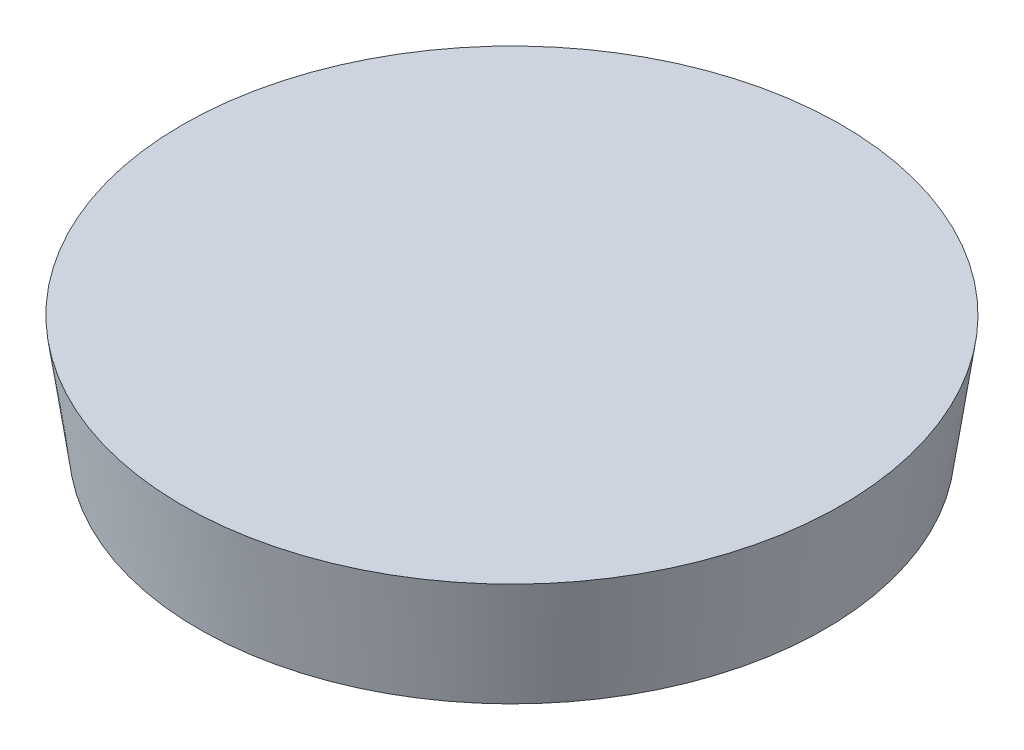
SolidWorks part; units mm, degrees
ref_plane "Front Plane" through (0, 0, 0) normal (0, 0, 1) x (1, 0, 0)
ref_plane "Top Plane" through (0, 0, 0) normal (0, 1, 0) x (1, 0, 0)
ref_plane "Right Plane" through (0, 0, 0) normal (1, 0, 0) x (0, 0, -1)
sketch "Sketch2" plane through (0, 0, 0) normal (0, 0, 1) x (1, 0, 0)
  line L0 (0, 0) -> (9.5, 0)
  line L1 (9.5, 0) -> (10, 3.5)
  line L2 (10, 3.5) -> (0, 3.5)
  line L3 (0, 3.5) -> (0, 0)
  dimension "D1" = 3.5
  dimension "D2" = 10
  dimension "D3" = 9.5
revolve "Revolve1" add sketch "Sketch2" angle 360 about L3
sketch "Sketch3" plane through (0, 0, 0) normal (0, -1, 0) x (1, 0, 0)
  circle A0 centre (0, 0) radius 4
extrude "Boss-Extrude1" add sketch "Sketch3" along normal blind 1.2
